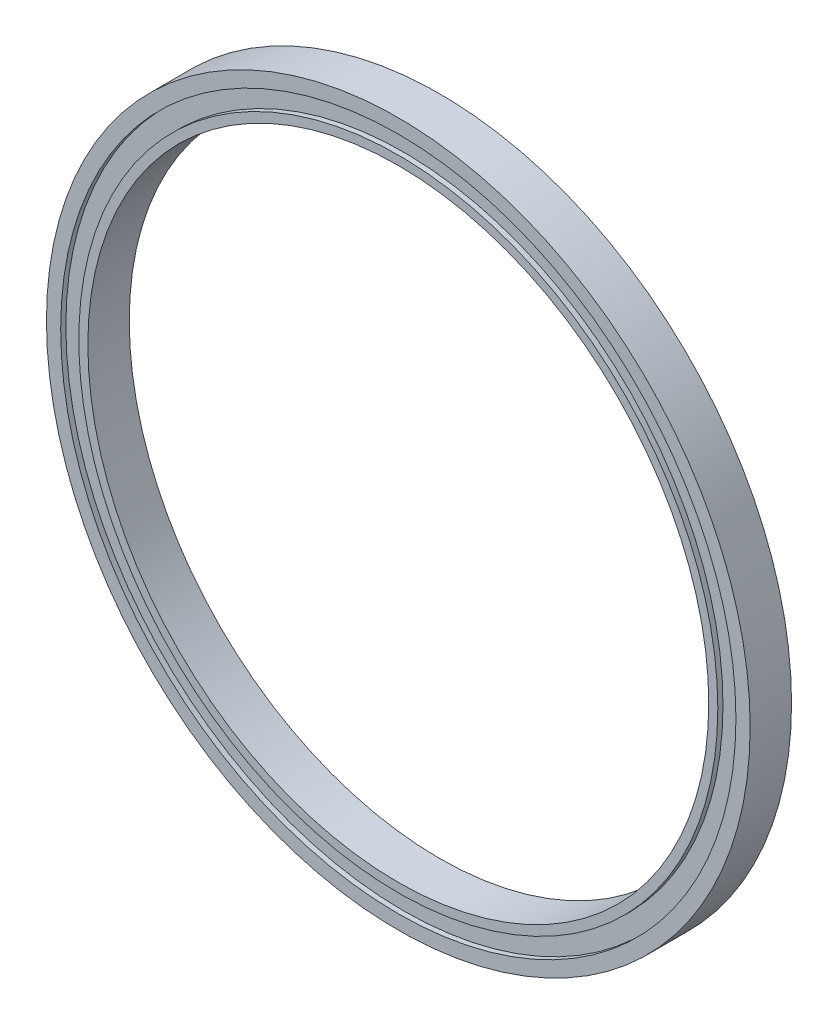
SolidWorks part; units mm, degrees
ref_plane "前视基准面" through (0, 0, 0) normal (0, 0, 1) x (1, 0, 0)
ref_plane "上视基准面" through (0, 0, 0) normal (0, 1, 0) x (1, 0, 0)
ref_plane "右视基准面" through (0, 0, 0) normal (1, 0, 0) x (0, 0, -1)
sketch "草图1" plane through (0, 0, 0) normal (0, 0, 1) x (1, 0, 0)
  circle A0 centre (0, 0) radius 60
  circle A1 centre (0, 0) radius 68
  dimension "D1" = 120
  dimension "D2" = 136
extrude "凸台-拉伸1" add sketch "草图1" along normal blind 8
sketch "草图2" plane through (0, 0, 8) normal (0, 0, 1) x (1, 0, 0)
  circle A0 centre (0, 0) radius 61.75
  circle A1 centre (0, 0) radius 65.25
  dimension "D1" = 123.5
  dimension "D2" = 130.5
extrude "切除-拉伸1" cut sketch "草图2" against normal blind 1
sketch "草图3" plane through (0, 0, 0) normal (0, 0, -1) x (-1, 0, 0)
  circle A0 centre (0, 0) radius 61.75
  circle A1 centre (0, 0) radius 65.25
  dimension "D1" = 123.5
  dimension "D2" = 130.5
extrude "切除-拉伸2" cut sketch "草图3" against normal blind 1
